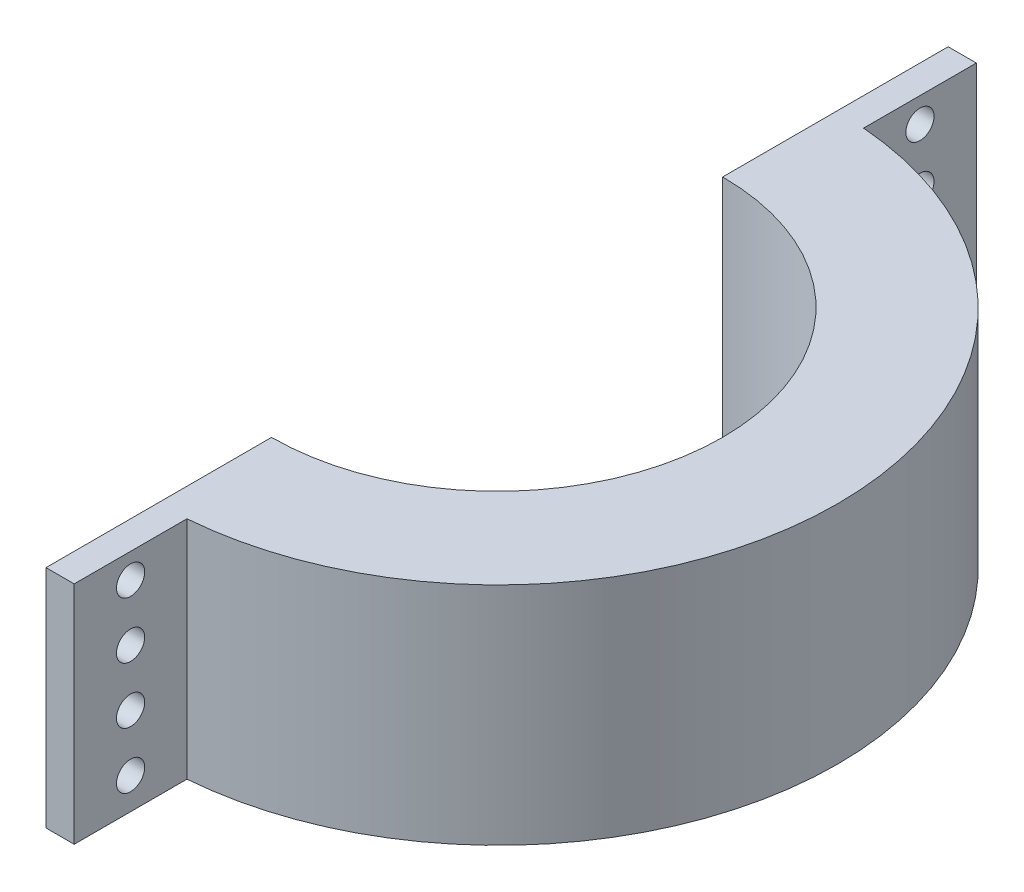
SolidWorks part; units mm, degrees
material "1060 Alloy"
ref_plane "Front Plane" through (0, 0, 0) normal (0, 0, 1) x (1, 0, 0)
ref_plane "Top Plane" through (0, 0, 0) normal (0, 1, 0) x (1, 0, 0)
ref_plane "Right Plane" through (0, 0, 0) normal (1, 0, 0) x (0, 0, -1)
sketch "Sketch1" plane through (0, 0, 0) normal (0, 1, 0) x (1, 0, 0)
  line L0 (0, -101.6) -> (0, -203.2)
  line L1 (0, 101.6) -> (0, 203.2)
  line L2 (0, 203.2) -> (12.7, 203.2)
  line L3 (0, -203.2) -> (12.7, -203.2)
  line L4 (12.7, 203.2) -> (12.7, 152.4)
  line L5 (12.7, -203.2) -> (12.7, -152.4)
  arc A0 (0, 101.6) -> (0, -101.6) centre (0, 0) cw
  arc A1 (12.7, 152.4) -> (12.7, -152.4) centre (0.5172, 0) cw
  dimension "D1" = 101.6
  dimension "D2" = 101.6
  dimension "D3" = 12.7
  dimension "D4" = 50.8
extrude "Boss-Extrude1" add sketch "Sketch1" along normal blind 101.6
sketch "Sketch2" plane through (12.7, 0, 0) normal (1, 0, 0) x (0, 0, -1)
  circle A0 centre (-177.8, 90.3803) radius 6.35
  circle A1 centre (-177.8, 64.9803) radius 6.35
  circle A2 centre (-177.8, 39.5803) radius 6.35
  circle A3 centre (-177.8, 14.1803) radius 6.35
  dimension "D1" = 12.7
  dimension "D2" = 4
extrude "Cut-Extrude1" cut sketch "Sketch2" against normal through all
sketch "Sketch3" plane through (12.7, 0, 0) normal (1, 0, 0) x (0, 0, -1)
  line L0 (-177.8, 90.3803) -> (248.942, 90.3803) construction
  circle A0 centre (177.8, 90.3803) radius 6.35
  circle A1 centre (177.8, 64.9803) radius 6.35
  circle A2 centre (177.8, 39.5803) radius 6.35
  circle A3 centre (177.8, 14.1803) radius 6.35
  dimension "D1" = 12.7
  dimension "D2" = 4
extrude "Cut-Extrude2" cut sketch "Sketch3" against normal through all
